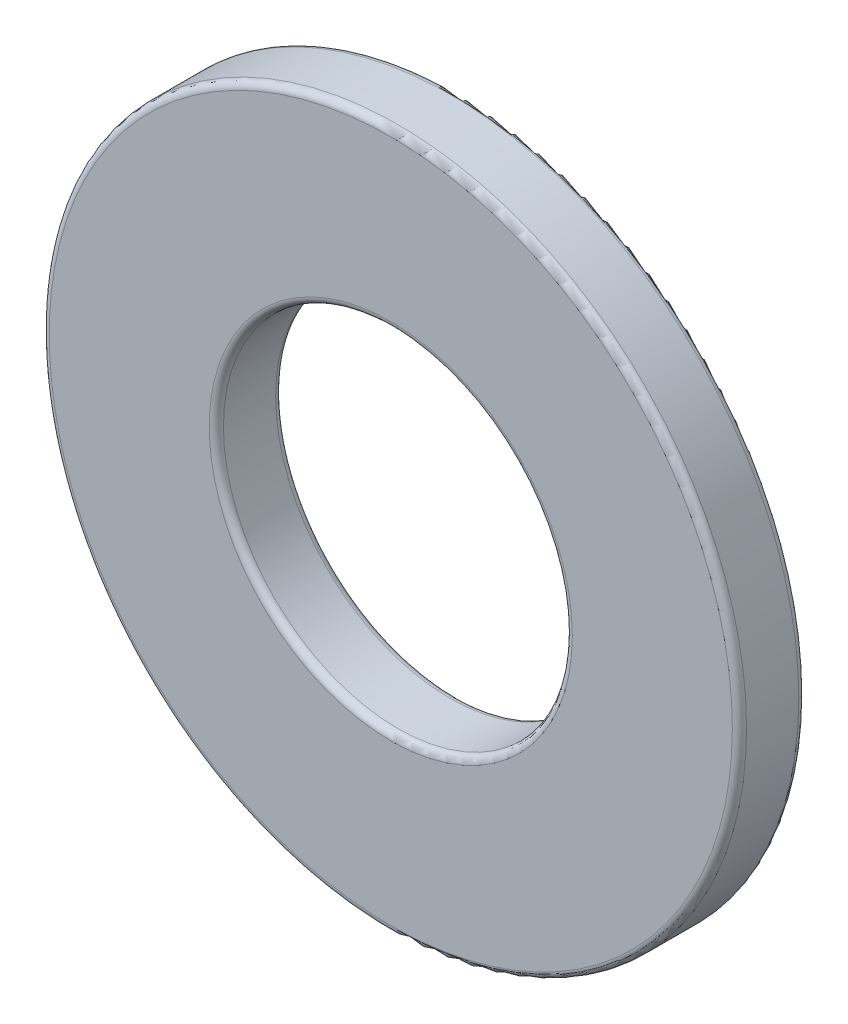
SolidWorks part; units mm, degrees
material "AISI 1020"
ref_plane "Front Plane" through (0, 0, 0) normal (1, 0, 0) x (0, 1, 0)
ref_plane "Top Plane" through (0, 0, 0) normal (0, 0, 1) x (0, 1, 0)
ref_plane "Right Plane" through (0, 0, 0) normal (0, 1, 0) x (-1, 0, 0)
sketch "Sketch1" plane through (0, 0, 0) normal (0, 0, 1) x (0, 1, 0)
  circle A0 centre (0, 0) radius 8.7312
  circle A1 centre (0, 0) radius 4.3688
  dimension "D1" = 8.7376
  dimension "D2" = 17.4625
extrude "Boss-Extrude1" add sketch "Sketch1" along normal mid plane 1.6637
fillet "Fillet2" radius 0.1778 4 edges at (4.3688, 0, 0.8318) (8.7312, 0, 0.8318) (4.3688, 0, -0.8318) (8.7312, 0, -0.8318)
